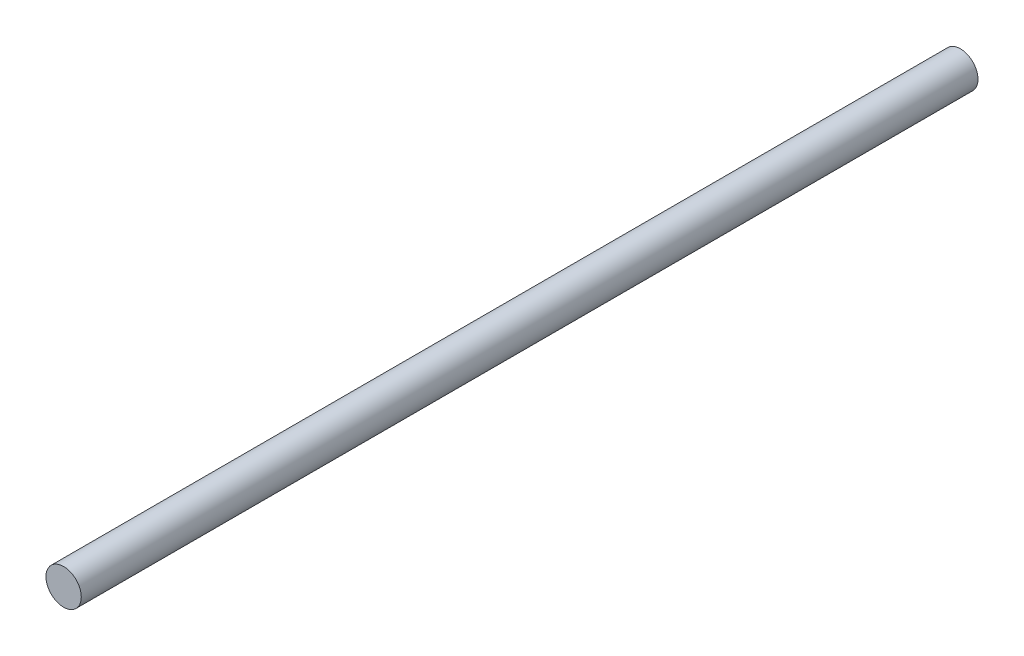
SolidWorks part; units mm, degrees
ref_plane "Plan de face" through (0, 0, 0) normal (0, 0, 1) x (1, 0, 0)
ref_plane "Plan de dessus" through (0, 0, 0) normal (0, 1, 0) x (1, 0, 0)
ref_plane "Plan de droite" through (0, 0, 0) normal (1, 0, 0) x (0, 0, -1)
sketch "Esquisse1" plane through (0, 0, 0) normal (0, 0, 1) x (1, 0, 0)
  circle A0 centre (-4.3438, 65.5622) radius 1.26
  arc A1 (-4.3557, 64.3023) -> (-4.332, 66.8221) centre (-4.3438, 65.5622) ccw construction
extrude "Extrusion1" add sketch "Esquisse1" against normal blind 64
